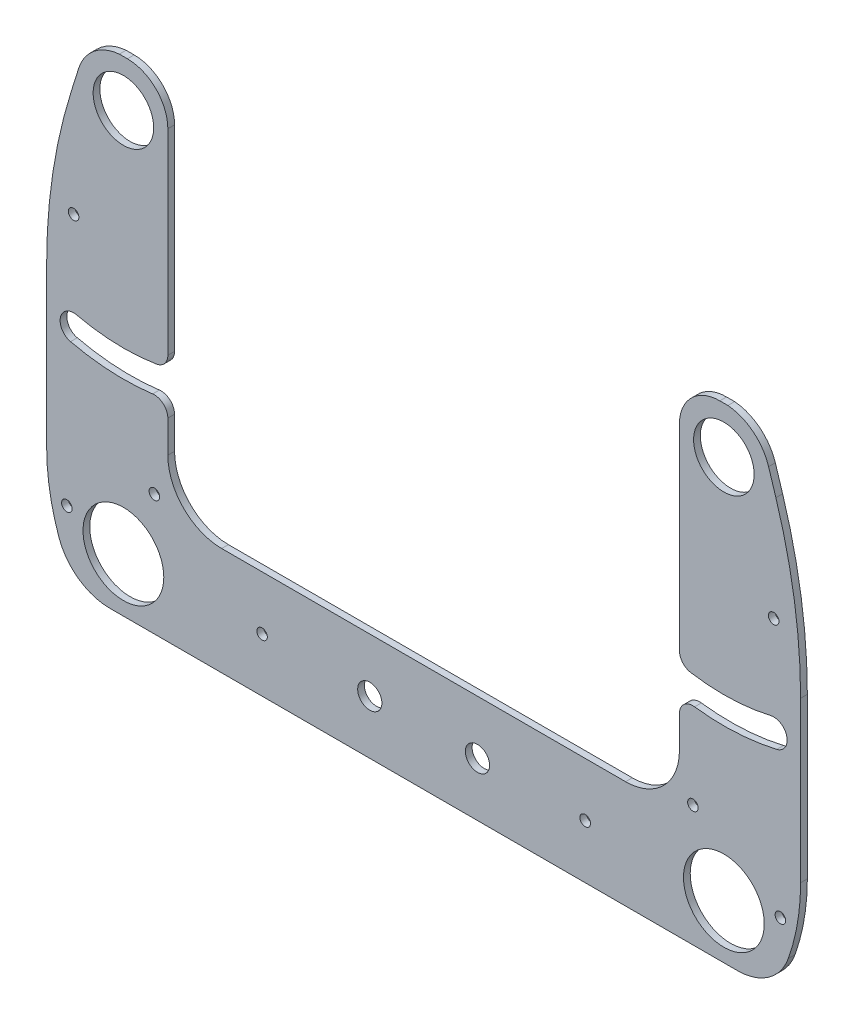
SolidWorks part; units mm, degrees
material "6061 Alloy"
ref_plane "Front Plane" through (0, 0, 0) normal (0, 0, 1) x (1, 0, 0)
ref_plane "Top Plane" through (0, 0, 0) normal (0, 1, 0) x (1, 0, 0)
ref_plane "Right Plane" through (0, 0, 0) normal (1, 0, 0) x (0, 0, -1)
sketch "Sketch1" plane through (0, 0, 0) normal (0, 0, 1) x (1, 0, 0)
  line L5 (120.65, -152.4) -> (120.65, -6.35)
  line L6 (127, 0) -> (171.45, 0) construction
  line L7 (177.8, -6.35) -> (177.8, -222.25)
  line L10 (0, -206.2199) -> (0, -63.6275) construction
  line L11 (-54.9244, 0) -> (300.6756, 0) construction
  line L13 (12.7, -177.8) -> (95.25, -177.8)
  line L14 (12.7, -228.6) -> (171.45, -228.6)
  line L15 (141.605, -22.0269) -> (141.605, -80.9091) construction
  line L16 (141.605, -22.0269) -> (141.605, -123.6269) construction
  line L19 (-141.605, -19.05) -> (-141.605, -77.9322) construction
  line L20 (141.605, -22.0269) -> (141.605, -203.2) construction
  line L22 (-120.65, -152.4) -> (-120.65, -6.35)
  line L23 (-12.7, -177.8) -> (-95.25, -177.8)
  line L24 (-12.7, -228.6) -> (-171.45, -228.6)
  line L25 (-177.8, -6.35) -> (-177.8, -222.25)
  line L26 (-12.7, -177.8) -> (12.7, -177.8)
  line L27 (-12.7, -228.6) -> (12.7, -228.6)
  line L28 (-177.8, -6.35) -> (-177.8, 6.35)
  line L29 (-165.1, 19.05) -> (-133.35, 19.05)
  line L30 (-120.65, 6.35) -> (-120.65, -6.35)
  line L31 (120.65, 6.35) -> (120.65, -6.35)
  line L32 (177.8, -6.35) -> (177.8, 6.35)
  line L33 (165.1, 19.05) -> (133.35, 19.05)
  arc A0 (95.25, -177.8) -> (120.65, -152.4) centre (95.25, -152.4) ccw
  arc A4 (120.65, -6.35) -> (127, 0) centre (127, -6.35) cw construction
  circle A8 centre (141.605, -22.0269) radius 14.2875
  circle A9 centre (141.605, -22.0269) radius 38.1 construction
  arc A10 (177.8, -6.35) -> (171.45, 0) centre (171.45, -6.35) ccw construction
  arc A11 (171.45, -228.6) -> (177.8, -222.25) centre (171.45, -222.25) ccw
  arc A14 (141.605, -79.1769) -> (120.9214, -75.3027) centre (141.605, -22.0269) ccw construction
  arc A15 (-141.605, -79.1769) -> (-120.9214, -75.3027) centre (-141.605, -22.0269) cw construction
  circle A16 centre (-141.605, -22.0269) radius 38.1 construction
  circle A17 centre (-141.605, -22.0269) radius 14.2875
  arc A19 (-95.25, -177.8) -> (-120.65, -152.4) centre (-95.25, -152.4) cw
  circle A20 centre (141.605, -123.6269) radius 38.1 construction
  circle A21 centre (-141.605, -123.6269) radius 38.1 construction
  arc A23 (-171.45, -228.6) -> (-177.8, -222.25) centre (-171.45, -222.25) cw
  circle A24 centre (-141.605, -203.2) radius 19.05
  circle A37 centre (141.605, -203.2) radius 19.05
  circle A39 centre (-76.2, -203.2) radius 2.4892
  circle A40 centre (76.2, -203.2) radius 2.4892
  circle A42 centre (-25.4, -203.2) radius 5.715
  arc A44 (-133.35, 19.05) -> (-120.65, 6.35) centre (-133.35, 6.35) cw
  arc A45 (-177.8, 6.35) -> (-165.1, 19.05) centre (-165.1, 6.35) cw
  arc A46 (133.35, 19.05) -> (120.65, 6.35) centre (133.35, 6.35) ccw
  arc A47 (177.8, 6.35) -> (165.1, 19.05) centre (165.1, 6.35) ccw
  circle A50 centre (-149.225, 6.35) radius 2.4892
  circle A53 centre (149.225, 6.35) radius 2.4892
  circle A54 centre (-168.275, -196.85) radius 2.4892
  circle A56 centre (168.275, -196.85) radius 2.4892
  circle A58 centre (-165.1, -76.2) radius 2.4892
  circle A59 centre (165.1, -76.2) radius 2.4892
  circle A60 centre (-127, -171.45) radius 2.4892
  circle A61 centre (127, -171.45) radius 2.4892
  circle A62 centre (25.4, -203.2) radius 5.715
  point P2 (177.8, -44.45)
  point P18 (177.8, 0)
  point P23 (177.8, -228.6)
  point P24 (177.8, -228.6)
  point P31 (177.8, 0)
  point P48 (-177.8, 0)
  point P49 (-177.8, -228.6)
  point P51 (-177.8, -44.45)
  point P78 (-141.605, -203.2)
  dimension "D6" = 25.4
  dimension "D7" = 6.35
  dimension "D8" = 6.35
  dimension "D9" = 177.8
  dimension "D10" = 28.575
  dimension "D12" = 76.2
  dimension "D13" = 57.15
  dimension "D15" = 38.1
  dimension "D18" = 76.2
  dimension "D21" = 4.9784
  dimension "D29" = 9.525
  dimension "D32" = 4.9784
  dimension "D35" = 11.43
  dimension "D40" = 12.7
  dimension "D43" = 4.9784
  dimension "D45" = 12.7
  dimension "D30" = 4.9784
  dimension "D41" = 4.9784
  dimension "D22" = 6.35
  dimension "D2" = 120.65
  dimension "D3" = 177.8
  dimension "D4" = 228.6
  dimension "D5" = 177.8
  dimension "D11" = 20.955
  dimension "`" = 22.0269
  dimension "D14" = 57.15
  dimension "D16" = 184.15
  dimension "D17" = 101.6
  dimension "D19" = 25.4
  dimension "D20" = 101.6
  dimension "D23" = 57.15
  dimension "D25" = 25.4
  dimension "D26" = 31.75
  dimension "D27" = 25.4
  dimension "D28" = 25.4
  dimension "D31" = 25.4
  dimension "D33" = 12.7
  dimension "D34" = 25.4
  dimension "D39" = 19.05
  dimension "D44" = 28.575
  dimension "D24" = 95.25
extrude "Boss-Extrude3" add sketch "Sketch1" along normal blind 3.175
sketch "Sketch2" plane through (0, 0, 3.175) normal (0, 0, 1) x (1, 0, 0)
  line L0 (177.8, -222.25) -> (177.8, 6.35) construction
  line L1 (-177.8, 19.05) -> (177.8, 19.05)
  line L2 (-177.8, 19.05) -> (-177.8, 0)
  line L3 (-177.8, 0) -> (177.8, 0)
  line L4 (177.8, 19.05) -> (177.8, 0)
  line L5 (-177.8, 6.35) -> (-177.8, -222.25) construction
  line L7 (-133.35, 19.05) -> (-165.1, 19.05) construction
  dimension "D1" = 19.05
extrude "Cut-Extrude1" cut sketch "Sketch2" against normal through all
fillet "Fillet1" radius 19.05 4 edges at (177.8, 0, 1.5875) (120.65, 0, 1.5875) (-120.65, 0, 1.5875) (-177.8, 0, 1.5875)
sketch "Sketch3" plane through (0, 0, 3.175) normal (0, 0, 1) x (1, 0, 0)
  line L2 (-177.8, -19.05) -> (-177.8, -222.25) construction
  line L3 (-158.75, 0) -> (-139.7, 0) construction
  line L4 (-177.8, -63.5) -> (-177.8, 0)
  line L5 (-177.8, 0) -> (-139.7, 0)
  line L6 (-177.8, -63.5) -> (-162.6988, -15.4039)
  arc A3 (-139.7, 0) -> (-162.6988, -15.4039) centre (-141.605, -22.0269) ccw
  dimension "D1" = 63.5
extrude "Cut-Extrude2" cut sketch "Sketch3" against normal through all
ref_plane "Plane1" through (0, 0, 0) normal (-1, 0, 0) x (0, 0, 1)
mirror "Mirror1" about plane through (0, 0, 0) normal (-1, 0, 0) of "Cut-Extrude2"
fillet "Fillet2" radius 254 2 edges at (177.8, -63.5, 1.5875) (-177.8, -63.5, 1.5875)
sketch "Sketch4" plane through (0, 0, 3.175) normal (0, 0, 1) x (1, 0, 0)
  line L0 (0, -177.8) -> (0, -13.685) construction
  line L5 (-177.8, -102.4383) -> (-177.8, -222.25) construction
  line L6 (-171.45, -228.6) -> (171.45, -228.6) construction
  line L7 (-177.8, -177.8) -> (-177.8, -228.6)
  line L8 (-177.8, -228.6) -> (-164.1882, -228.6)
  line L9 (177.8, -177.8) -> (177.8, -228.6)
  line L10 (177.8, -228.6) -> (164.1882, -228.6)
  circle A0 centre (-76.2, -177.8) radius 101.6 construction
  arc A1 (-177.8, -177.8) -> (-164.1882, -228.6) centre (-76.2, -177.8) ccw
  arc A2 (177.8, -177.8) -> (164.1882, -228.6) centre (76.2, -177.8) cw
  dimension "D1" = 203.2
  dimension "D2" = 50.8
extrude "Cut-Extrude3" cut sketch "Sketch4" against normal through all contours L8 A1 L7 | L9 L10 A2
fillet "Fillet3" radius 25.4 2 edges at (164.1882, -228.6, 1.5875) (-164.1882, -228.6, 1.5875)
sketch "Sketch5" plane through (0, 0, 3.175) normal (0, 0, 1) x (1, 0, 0)
  line L2 (-120.65, -129.7962) -> (-120.65, -116.8262)
  line L5 (120.65, -129.7962) -> (120.65, -116.8262)
  line L6 (120.65, -19.05) -> (120.65, -152.4) construction
  line L7 (177.8, -177.8) -> (177.8, -102.4383) construction
  line L8 (0, -203.7675) -> (0, -15.567) construction
  circle A4 centre (141.605, -22.0269) radius 103.4377 construction
  arc A5 (120.65, -116.8262) -> (163.6577, -116.5769) centre (141.605, -22.0269) ccw
  arc A6 (120.65, -129.7962) -> (166.5423, -128.9449) centre (141.605, -22.0269) ccw
  arc A9 (166.5423, -128.9449) -> (163.6577, -116.5769) centre (165.1, -122.7609) ccw
  arc A10 (-120.65, -129.7962) -> (-166.5423, -128.9449) centre (-141.605, -22.0269) cw
  arc A11 (-120.65, -116.8262) -> (-163.6577, -116.5769) centre (-141.605, -22.0269) cw
  arc A12 (-166.5423, -128.9449) -> (-163.6577, -116.5769) centre (-165.1, -122.7609) cw
  dimension "D1" = 97.0877
  dimension "D2" = 109.7877
  dimension "D4" = 12.7
  dimension "D3" = 206.8754
extrude "Cut-Extrude4" cut sketch "Sketch5" against normal through all contours A10 A12 A11 L2 | A9 A5 L5 A6
fillet "Fillet4" radius 6.35 4 edges at (120.65, -129.7962, 1.5875) (120.65, -116.8262, 1.5875) (-120.65, -129.7962, 1.5875) (-120.65, -116.8262, 1.5875)
sketch "Sketch6" plane through (0, 0, 0) normal (0, 0, -1) x (-1, 0, 0)
  line L1 (-743.0643, -231.14) -> (49256.9357, -231.14) construction
  line L2 (-180.34, -1269.6837) -> (-180.34, 48730.3163) construction
  line L3 (148.042, -228.6) -> (-148.042, -228.6) construction
  circle A0 centre (-76.2, -203.2) radius 2.4892 construction
  point P11 (-180.34, -231.14)
  dimension "D3" = 104.14
  dimension "D1" = 2.54
